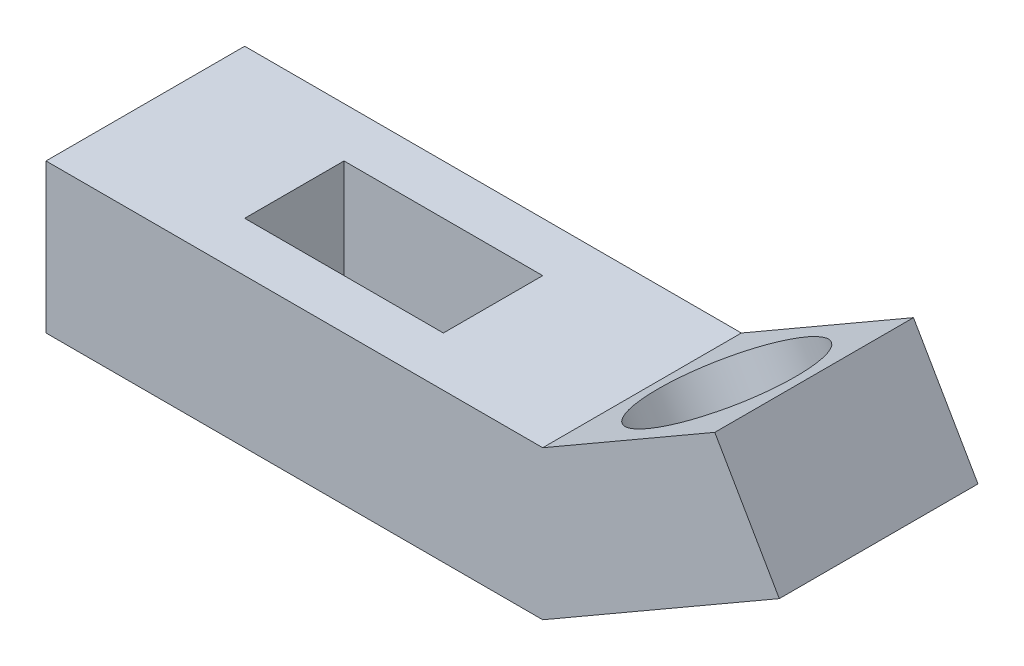
SolidWorks part; units mm, degrees
ref_plane "前视基准面" through (0, 0, 0) normal (0, 0, 1) x (1, 0, 0)
ref_plane "上视基准面" through (0, 0, 0) normal (0, 1, 0) x (1, 0, 0)
ref_plane "右视基准面" through (0, 0, 0) normal (1, 0, 0) x (0, 0, -1)
sketch "草图1" plane through (0, 0, 0) normal (0, 1, 0) x (1, 0, 0)
  line L1 (10, 5) -> (-10, 5)
  line L2 (10, 5) -> (10, -5)
  line L3 (10, -5) -> (-10, -5)
  line L4 (-10, 5) -> (-10, -5)
  line L5 (10, 5) -> (-10, -5) construction
  line L6 (10, -5) -> (-10, 5) construction
  line L7 (25, 10) -> (-25, 10)
  line L8 (25, 10) -> (25, -10)
  line L9 (25, -10) -> (-25, -10)
  line L10 (-25, 10) -> (-25, -10)
  line L11 (25, 10) -> (-25, -10) construction
  line L12 (25, -10) -> (-25, 10) construction
  point P0 (0, 0)
  point P6 (0, 0)
extrude "凸台-拉伸1" add sketch "草图1" along normal blind 15
sketch "草图2" plane through (0, 0, 10) normal (0, 0, 1) x (1, 0, 0)
  line L0 (25, 15) -> (42.3205, 25)
  line L1 (42.3205, 25) -> (48.8157, 13.75)
  line L2 (48.8157, 13.75) -> (25, 0)
  line L3 (25, 0) -> (25, 15)
extrude "凸台-拉伸2" add sketch "草图2" against normal up to surface (20 mm away) up to face at (0, 7.5, -10)
sketch "草图3" plane through (-0.2452, 0.4247, 0) normal (-0.5, 0.866, 0) x (0.866, 0.5, 0)
  circle A0 centre (39, 0) radius 8
  point P2 (0, 0)
extrude "切除-拉伸1" cut sketch "草图3" against normal through all contours A0
